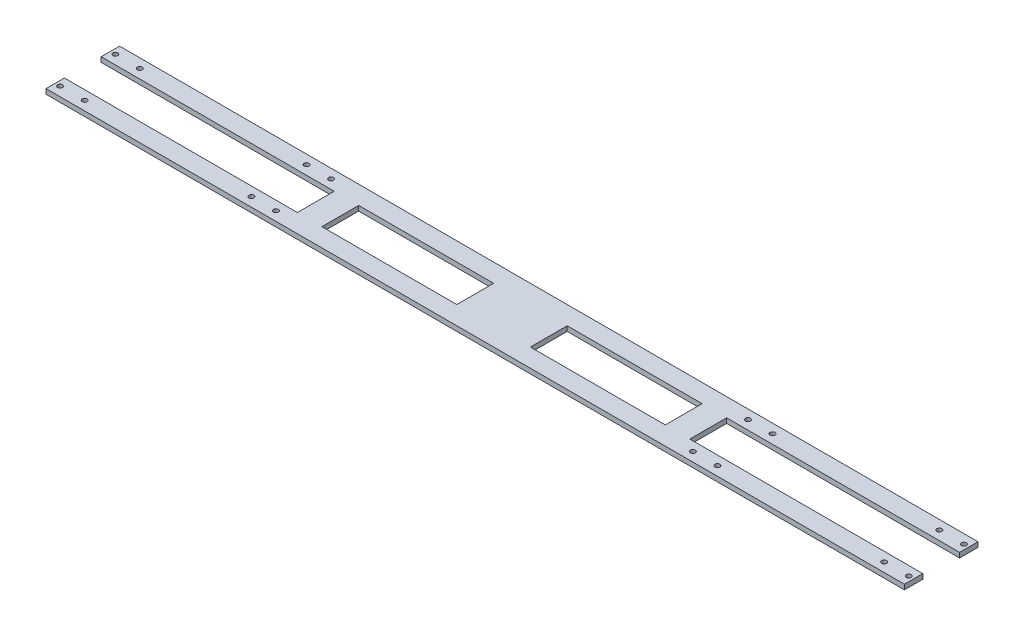
SolidWorks part; units mm, degrees
ref_plane "前视基准面" through (0, 0, 0) normal (0, 0, 1) x (1, 0, 0)
ref_plane "上视基准面" through (0, 0, 0) normal (0, 1, 0) x (1, 0, 0)
ref_plane "右视基准面" through (0, 0, 0) normal (1, 0, 0) x (0, 0, -1)
other "Configuration Table"
sketch "草图1" plane through (0, 0, 0) normal (0, 1, 0) x (1, 0, 0)
  line L1 (-350, -30) -> (350, -30)
  line L2 (-350, -30) -> (-350, 30)
  line L3 (-350, 30) -> (350, 30)
  line L4 (350, -30) -> (350, 30)
  line L5 (-350, -30) -> (350, 30) construction
  line L6 (-350, 30) -> (350, -30) construction
  line L7 (-140, -15) -> (140, -15)
  line L8 (-140, -15) -> (-140, 15)
  line L9 (-140, 15) -> (140, 15)
  line L10 (140, -15) -> (140, 15)
  line L11 (-140, -15) -> (140, 15) construction
  line L12 (-140, 15) -> (140, -15) construction
  point P0 (0, 0)
  point P6 (0, 0)
  dimension "D1" = 700
  dimension "D2" = 60
  dimension "D3" = 30
  dimension "D4" = 280
extrude "凸台-拉伸1" add sketch "草图1" along normal blind 4
sketch "草图2" plane through (0, 4, 0) normal (0, 1, 0) x (1, 0, 0)
  line L0 (-350, 30) -> (-350, -30) construction
  line L1 (-350, 15) -> (-160, 15)
  line L2 (-350, 15) -> (-350, -15)
  line L3 (-350, -15) -> (-160, -15)
  line L4 (-160, 15) -> (-160, -15)
  line L5 (140, 15) -> (-140, 15) construction
  line L6 (-140, -15) -> (140, -15) construction
  line L7 (-140, 15) -> (-140, -15) construction
  dimension "D1" = 20
extrude "切除-拉伸1" cut sketch "草图2" against normal blind 4
mirror "镜向1" about plane through (0, 0, 0) normal (1, 0, 0) of "切除-拉伸1"
sketch "草图3" plane through (0, 4, 0) normal (0, 1, 0) x (1, 0, 0)
  line L0 (350, 30) -> (-350, 30) construction
  line L2 (-350, 30) -> (-350, 15) construction
  circle A0 centre (-190, 22.5) radius 2
  circle A1 centre (-170, 22.5) radius 2
  circle A2 centre (-346, 22.5) radius 2
  circle A3 centre (-326, 22.5) radius 2
  point P6 (0, 0)
  dimension "D2" = 4
  dimension "D3" = 170
  dimension "D5" = 4
  dimension "D1" = 7.5
  dimension "D4" = 20
  dimension "D6" = 20
  dimension "D7" = 7.5
  dimension "D8" = 4
extrude "切除-拉伸2" cut sketch "草图3" against normal blind 4
mirror "镜向2" about plane through (0, 0, 0) normal (1, 0, 0) of "切除-拉伸2" second plane through (0, 0, 0) second plane normal (0, 0, 1)
sketch "草图4" plane through (0, 4, 0) normal (0, 1, 0) x (1, 0, 0)
  line L0 (140, 15) -> (-140, 15) construction
  line L1 (-30, -15) -> (30, -15)
  line L2 (-30, -15) -> (-30, 15)
  line L3 (-30, 15) -> (30, 15)
  line L4 (30, -15) -> (30, 15)
  line L5 (-30, -15) -> (30, 15) construction
  line L6 (-30, 15) -> (30, -15) construction
  point P0 (0, 0)
  point P7 (0, 0)
  dimension "D1" = 60
extrude "凸台-拉伸2" add sketch "草图4" against normal blind 4
